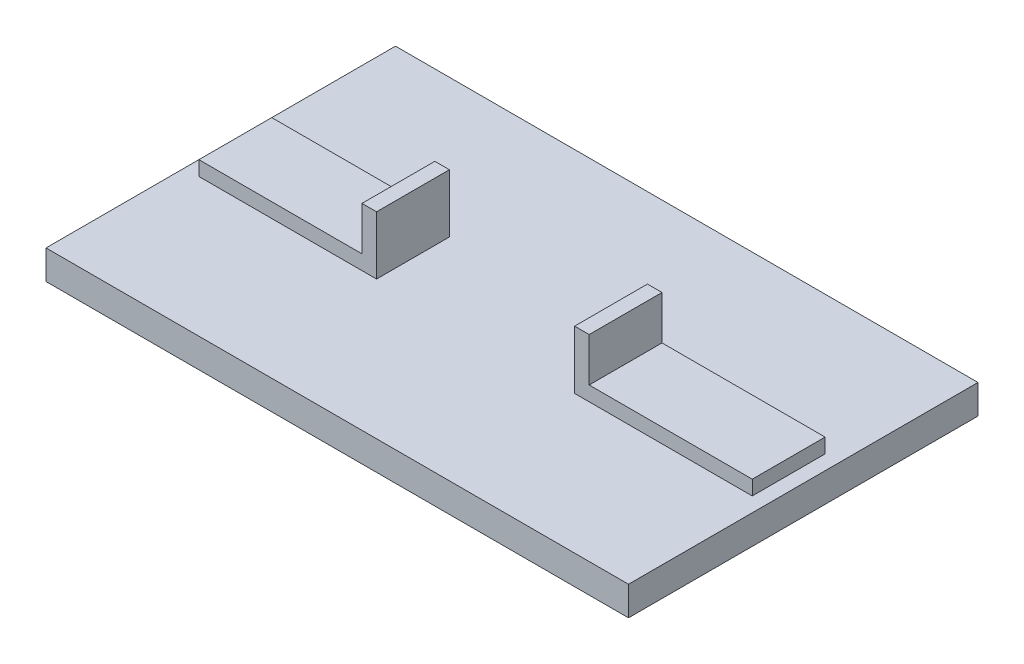
SolidWorks part; units mm, degrees
ref_plane "Front Plane" through (0, 0, 0) normal (0, 0, 1) x (1, 0, 0)
ref_plane "Top Plane" through (0, 0, 0) normal (0, 1, 0) x (1, 0, 0)
ref_plane "Right Plane" through (0, 0, 0) normal (1, 0, 0) x (0, 0, -1)
sketch "Sketch2" plane through (0, 0, 0) normal (0, 1, 0) x (1, 0, 0)
  line L0 (0, 30) -> (0, -30) construction
  line L1 (-50, 30) -> (50, 30)
  line L2 (-50, 30) -> (-50, -30)
  line L3 (-50, -30) -> (50, -30)
  line L4 (50, 30) -> (50, -30)
  point P0 (0, 0)
  dimension "D1" = 60
  dimension "D2" = 100
extrude "Boss-Extrude1" add sketch "Sketch2" along normal blind 5
sketch "Sketch3" plane through (0, 5, 0) normal (0, 1, 0) x (1, 0, 0)
  line L0 (-50, 0) -> (50, 0) construction
  line L1 (-50, 30) -> (-50, -30) construction
  line L2 (50, -30) -> (50, 30) construction
  line L3 (-25, -6.254) -> (-50, -6.254) construction
  line L4 (-50, 8.754) -> (-25, 8.754) construction
  line L5 (-25, 8.754) -> (-25, 6.254) construction
  line L6 (-25, 6.254) -> (-50, 6.254) construction
  line L7 (-25, -8.754) -> (-25, -6.254) construction
  line L8 (-50, -8.754) -> (-25, -8.754) construction
  line L9 (0, 30) -> (0, -30) construction
  line L10 (50, 30) -> (-50, 30) construction
  line L11 (-50, -30) -> (50, -30) construction
  line L12 (50, -8.754) -> (25, -8.754) construction
  line L13 (25, -8.754) -> (25, -6.254) construction
  line L14 (25, 6.254) -> (50, 6.254) construction
  line L15 (25, 8.754) -> (25, 6.254) construction
  line L16 (50, 8.754) -> (25, 8.754) construction
  line L17 (25, -6.254) -> (50, -6.254) construction
  dimension "D1" = 2.5
  dimension "D2" = 6.254
  dimension "D3" = 25
sketch "Sketch4" plane through (0, 5, 0) normal (0, 1, 0) x (1, 0, 0)
  line L0 (-47.5, 6.254) -> (-19.5, 6.254)
  line L1 (-19.5, 6.254) -> (-19.5, -6.254)
  line L2 (-19.5, -6.254) -> (-47.5, -6.254)
  line L3 (-47.5, -6.254) -> (-47.5, 6.254)
  line L4 (0, 30) -> (0, -30) construction
  line L5 (50, 30) -> (-50, 30) construction
  line L6 (-50, -30) -> (50, -30) construction
  line L7 (47.5, -6.254) -> (47.5, 6.254)
  line L8 (19.5, -6.254) -> (47.5, -6.254)
  line L9 (19.5, 6.254) -> (19.5, -6.254)
  line L10 (47.5, 6.254) -> (19.5, 6.254)
  line L11 (-50, 30) -> (-50, -30) construction
  line L12 (-25, 6.254) -> (-50, 6.254) construction
  line L13 (-25, -6.254) -> (-50, -6.254) construction
  dimension "D1" = 2.5
  dimension "D2" = 28
extrude "Boss-Extrude2" add sketch "Sketch4" along normal blind 2.5
sketch "Sketch5" plane through (0, 5, 0) normal (0, 1, 0) x (1, 0, 0)
  line L0 (-19.5, 6.254) -> (-47.5, 6.254) construction
  line L1 (-19.5, 6.254) -> (-17, 6.254)
  line L2 (-19.5, 6.254) -> (-19.5, -6.254)
  line L3 (-19.5, -6.254) -> (-17, -6.254)
  line L4 (-17, 6.254) -> (-17, -6.254)
  line L5 (-47.5, -6.254) -> (-19.5, -6.254) construction
  line L7 (-47.5, 6.254) -> (-47.5, -6.254) construction
  line L8 (0, 30) -> (0, -30) construction
  line L9 (50, 30) -> (-50, 30) construction
  line L10 (17, 6.254) -> (17, -6.254)
  line L11 (19.5, -6.254) -> (17, -6.254)
  line L12 (19.5, 6.254) -> (19.5, -6.254)
  line L13 (19.5, 6.254) -> (17, 6.254)
  dimension "D1" = 28
  dimension "D2" = 2.5
extrude "Boss-Extrude3" add sketch "Sketch5" along normal blind 10
equation "\"Width\" = 100mm"
equation "\"T\"= 2.5mm"
equation "\"D1@Sketch3\"=\"T\""
equation "\"Clear\"= 0.01in"
equation "\"D2@Sketch3\"=6+\"Clear\""
equation "\"D1@Sketch4\"=\"T\""
